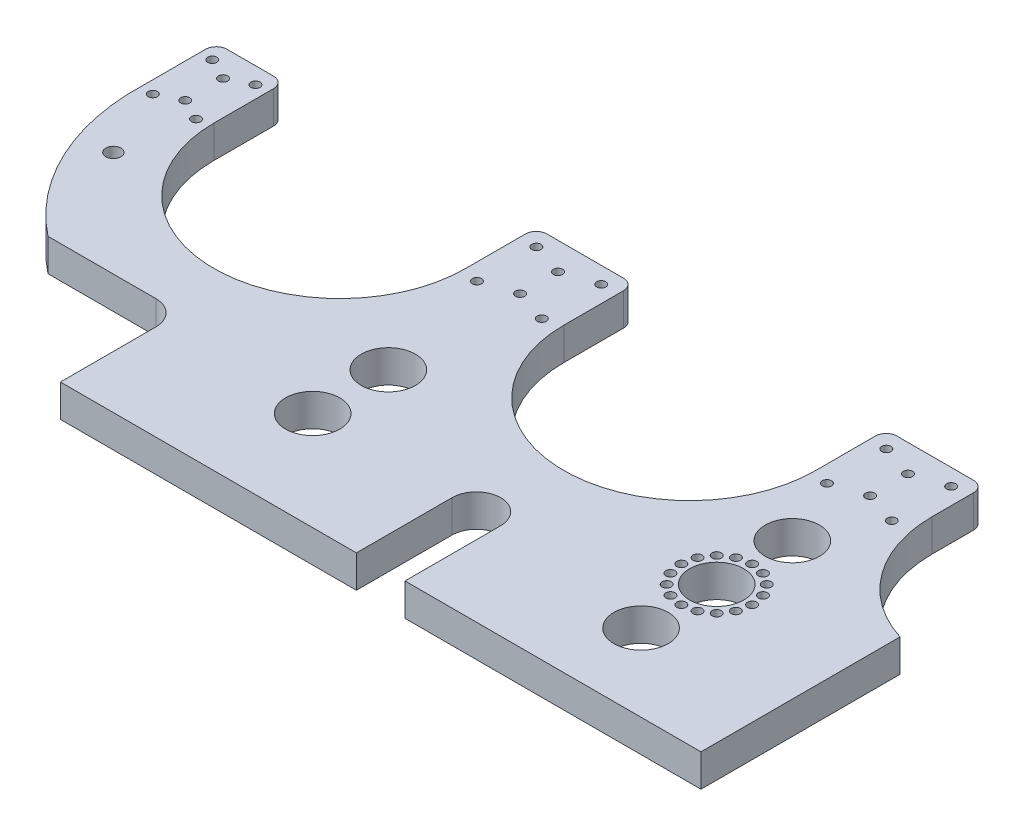
SolidWorks part; units mm, degrees
ref_plane "Front Plane" through (0, 0, 0) normal (0, 0, 1) x (1, 0, 0)
ref_plane "Top Plane" through (0, 0, 0) normal (0, 1, 0) x (1, 0, 0)
ref_plane "Right Plane" through (0, 0, 0) normal (1, 0, 0) x (0, 0, -1)
sketch "Sketch1" plane through (0, 0, 0) normal (0, 1, 0) x (1, 0, 0)
  line L0 (0, 0) -> (273.87, 0)
  line L1 (318.87, 0) -> (592.74, 0)
  line L2 (592.74, 0) -> (592.74, 184.1921)
  line L3 (273.87, 0) -> (273.87, 88.5021)
  line L4 (318.87, 0) -> (318.87, 88.5021)
  line L5 (0, 0) -> (0, 88.5021)
  line L6 (-22.5, 111.0021) -> (-122.5, 111.0021)
  line L7 (-189.5, 343.7421) -> (-146.5, 343.7421)
  line L8 (-199.5, 333.7421) -> (-199.5, 260.9762)
  line L9 (-136.5, 333.7421) -> (-136.5, 278.472)
  line L10 (96.5, 278.472) -> (96.5, 333.7421)
  line L11 (106.5, 343.7421) -> (177.37, 343.7421)
  line L12 (187.37, 333.7421) -> (187.37, 278.472)
  line L13 (420.37, 278.472) -> (420.37, 333.7421)
  line L14 (430.37, 343.7421) -> (501.25, 343.7421)
  line L15 (511.25, 333.7421) -> (511.25, 295.3071)
  arc A1 (273.87, 88.5021) -> (318.87, 88.5021) centre (296.37, 88.5021) cw
  arc A2 (0, 88.5021) -> (-22.5, 111.0021) centre (-22.5, 88.5021) ccw
  circle A6 centre (-188, 328.49) radius 4.25
  circle A7 centre (-148, 328.49) radius 4.25
  circle A8 centre (-188, 273.49) radius 4.25
  circle A9 centre (-148, 273.49) radius 4.25
  circle A10 centre (-168, 318.49) radius 4.25
  circle A11 centre (-168, 283.49) radius 4.25
  arc A12 (-189.5, 343.7421) -> (-199.5, 333.7421) centre (-189.5, 333.7421) ccw
  arc A13 (-136.5, 333.7421) -> (-146.5, 343.7421) centre (-146.5, 333.7421) ccw
  arc A14 (-136.5, 278.472) -> (96.5, 278.472) centre (-20, 278.472) ccw
  arc A16 (-199.5, 260.9762) -> (-122.5, 111.0021) centre (2.2078, 269.7836) ccw
  arc A17 (187.37, 278.472) -> (420.37, 278.472) centre (303.87, 278.472) ccw
  circle A18 centre (111.935, 328.49) radius 4.25
  circle A19 centre (171.935, 328.49) radius 4.25
  circle A20 centre (111.935, 273.49) radius 4.25
  circle A21 centre (171.935, 273.49) radius 4.25
  circle A22 centre (141.935, 318.49) radius 4.25
  circle A23 centre (141.935, 283.49) radius 4.25
  arc A24 (106.5, 343.7421) -> (96.5, 333.7421) centre (106.5, 333.7421) ccw
  arc A25 (187.37, 333.7421) -> (177.37, 343.7421) centre (177.37, 333.7421) ccw
  circle A26 centre (435.81, 328.49) radius 4.25
  circle A27 centre (495.81, 328.49) radius 4.25
  circle A28 centre (435.81, 273.49) radius 4.25
  circle A29 centre (495.81, 273.49) radius 4.25
  circle A30 centre (465.81, 318.49) radius 4.25
  circle A31 centre (465.81, 283.49) radius 4.25
  arc A32 (511.25, 295.3071) -> (592.74, 184.1921) centre (627.75, 295.3071) ccw
  arc A33 (430.37, 343.7421) -> (420.37, 333.7421) centre (430.37, 333.7421) ccw
  arc A36 (511.25, 333.7421) -> (501.25, 343.7421) centre (501.25, 333.7421) ccw
  circle A37 centre (465.81, 71.5) radius 25.1
  circle A38 centre (465.81, 141.5) radius 25.1
  circle A39 centre (465.81, 211.5) radius 25.1
  circle A40 centre (465.81, 141.5) radius 32.75 construction
  circle A41 centre (465.81, 141.5) radius 40.4
  circle A42 centre (465.81, 174.25) radius 4.25
  circle A43 centre (453.2771, 171.7571) radius 4.25
  circle A44 centre (442.6523, 164.6577) radius 4.25
  circle A45 centre (435.5529, 154.0329) radius 4.25
  circle A46 centre (433.06, 141.5) radius 4.25
  circle A47 centre (453.2771, 111.2429) radius 4.25
  circle A48 centre (442.6523, 118.3423) radius 4.25
  circle A49 centre (435.5529, 128.9671) radius 4.25
  circle A50 centre (465.81, 108.75) radius 4.25
  circle A51 centre (478.3429, 111.2429) radius 4.25
  circle A52 centre (488.9677, 118.3423) radius 4.25
  circle A53 centre (496.0671, 128.9671) radius 4.25
  circle A54 centre (498.56, 141.5) radius 4.25
  circle A55 centre (496.0671, 154.0329) radius 4.25
  circle A56 centre (488.9677, 164.6577) radius 4.25
  circle A57 centre (478.3429, 171.7571) radius 4.25
  circle A58 centre (141.935, 161.5) radius 25.1
  circle A59 centre (141.935, 91.5) radius 25.1
  circle A60 centre (-159.5, 208.5021) radius 7
  dimension "D5" = 63
  dimension "D7" = 22.5
  dimension "D8" = 11.5
  dimension "D11" = 8.5
  dimension "D13" = 35
  dimension "D16" = 55
  dimension "D17" = 40
  dimension "D12" = 55
  dimension "D21" = 15.2521
  dimension "D22" = 10
  dimension "D23" = 10
  dimension "D24" = 116.5
  dimension "D25" = 11.5
  dimension "D26" = 201.9
  dimension "D28" = 116.5
  dimension "D29" = 8.5
  dimension "D34" = 10
  dimension "D27" = 10
  dimension "D42" = 8.5
  dimension "D50" = 116.5
  dimension "D55" = 20
  dimension "D41" = 10
  dimension "D59" = 50.2
  dimension "D60" = 71.5
  dimension "D62" = 0
  dimension "D65" = 65.5
  dimension "D66" = 7.65
  dimension "D67" = 91.5
  dimension "D74" = 8.5
  dimension "D69" = 50.2
  dimension "D44" = 14
  dimension "D1" = 273.87
  dimension "D2" = 45
  dimension "D3" = 592.74
  dimension "D4" = 184.1921
  dimension "D6" = 88.5021
  dimension "D9" = 100
  dimension "D10" = 111.0021
  dimension "D14" = 0
  dimension "D15" = 162.4879
  dimension "D18" = 40
  dimension "D19" = 10
  dimension "D20" = 20
  dimension "D30" = 60
  dimension "D31" = 35
  dimension "D32" = 60
  dimension "D33" = 55
  dimension "D35" = 90.87
  dimension "D36" = 15.435
  dimension "D37" = 15.435
  dimension "D38" = 15.435
  dimension "D39" = 15.435
  dimension "D40" = 30
  dimension "D43" = 60
  dimension "D45" = 55
  dimension "D46" = 55
  dimension "D47" = 30
  dimension "D48" = 40
  dimension "D49" = 30
  dimension "D51" = 97.5
  dimension "D52" = 15.44
  dimension "D53" = 15.44
  dimension "D54" = 10
  dimension "D58" = 0
  dimension "D61" = 792.24
  dimension "D63" = 70
  dimension "D64" = 70
  dimension "D68" = 161.5
  dimension "D70" = 141.935
  dimension "D71" = 146.94
extrude "Boss-Extrude1" add sketch "Sketch1" along normal blind 30 contours L15 A36 L14 A33 L13 A17 L12 A25 L11 A24 L10 A14 L9 A13 L7 A12 L8 A16 L6 A2 L5 L0 L3 A1 L4 L1 L2 A32 A59 A58 A41 A39 A37 A6 A7 A8 A9 A10 A11 | A41 A56 A54 A53 A52 A51 A49 A47 A46 A45 A44 A43 A42 A38 A48 A50 A55 A57
